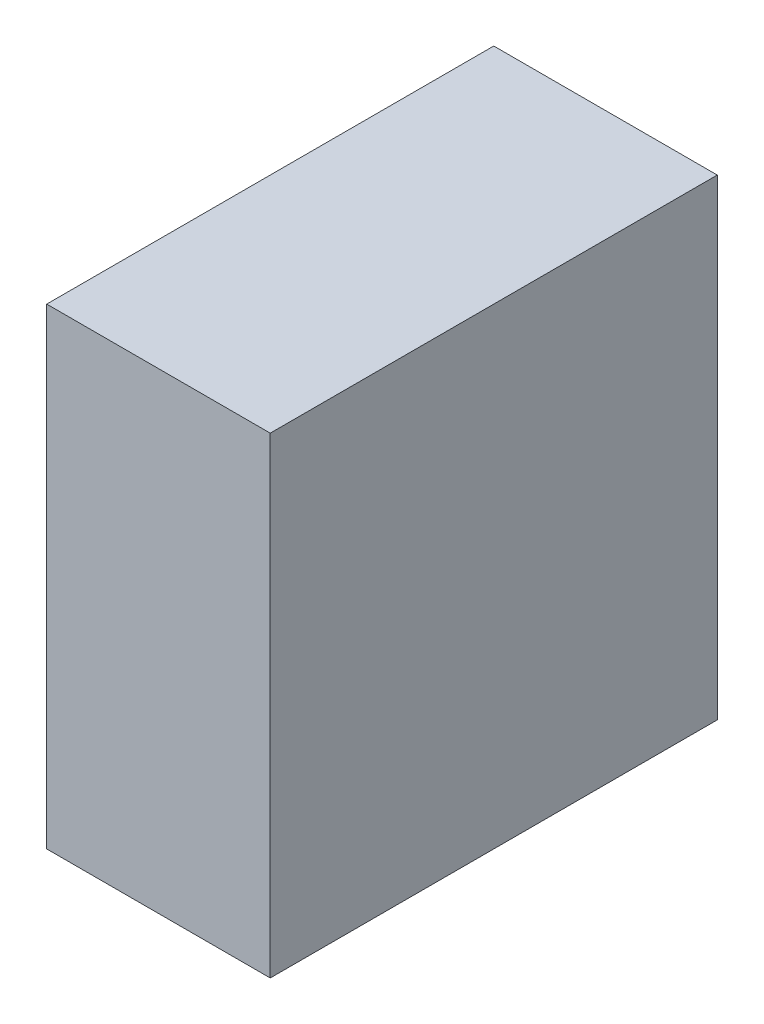
SolidWorks part; units mm, degrees
material "Low Carbon Steel"
ref_plane "Front Plane" through (0, 0, 0) normal (0, 0, 1) x (1, 0, 0)
ref_plane "Top Plane" through (0, 0, 0) normal (0, 1, 0) x (1, 0, 0)
ref_plane "Right Plane" through (0, 0, 0) normal (1, 0, 0) x (0, 0, -1)
sketch "Sketch1" plane through (0, 0, 0) normal (0, 0, 1) x (1, 0, 0)
  line L1 (-28.575, 120.65) -> (28.575, 120.65)
  line L2 (-28.575, 120.65) -> (-28.575, 0)
  line L3 (-28.575, 0) -> (28.575, 0)
  line L4 (28.575, 120.65) -> (28.575, 0)
  dimension "D1" = 57.15
  dimension "D2" = 120.65
extrude "Boss-Extrude1" add sketch "Sketch1" along normal mid plane 114.3
other "Freeze***"
